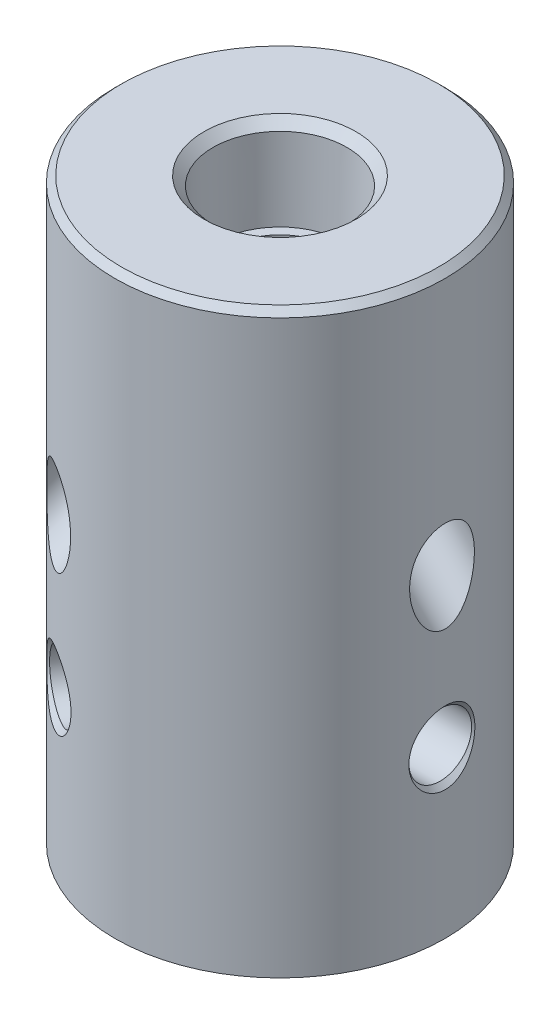
SolidWorks part; units mm, degrees
ref_plane "Plane1" through (0, 0, 0) normal (0, 0, 1) x (1, 0, 0)
ref_plane "Plane2" through (0, 0, 0) normal (0, 1, 0) x (1, 0, 0)
ref_plane "Plane3" through (0, 0, 0) normal (1, 0, 0) x (0, 0, -1)
sketch "Sketch1" plane through (0, 0, 0) normal (0, 0, 1) x (1, 0, 0)
  line L0 (0, -15.4434) -> (0, 76.0833) construction
  line L1 (0, 0) -> (2.54, 0)
  line L2 (2.54, 0) -> (12.7, 1.7915)
  line L3 (12.7, 1.7915) -> (12.7, 45.7335)
  line L4 (12.192, 46.2415) -> (0, 46.2415)
  line L5 (0, 46.2415) -> (0, 0)
  line L6 (6.35, 0.6718) -> (3.9132, 14.4915) construction
  line L7 (12.7, 14.4915) -> (3.9132, 14.4915) construction
  line L8 (12.7, 25.9215) -> (0, 38.6215) construction
  line L9 (12.7, 45.7335) -> (12.192, 46.2415)
  point P7 (12.7, 46.2415)
  dimension "D1" = 5.08
  dimension "D2" = 6.35
  dimension "D3" = 10
  dimension "D4" = 25.4
  dimension "D5" = 44.45
  dimension "D6" = 12.7
  dimension "D7" = 20.32
  dimension "D8" = 45
revolve "Revolve1" add sketch "Sketch1" angle 360 about L5
hole_wizard "1/8 NPT Tapped Hole1" positions "Sketch5" profile "Sketch4" size "1/8" standard "ANSI Inch"
sketch "Sketch5" plane through (0, 46.2415, 0) normal (0, 1, 0) x (1, 0, 0)
  point P0 (0, 0)
sketch "Sketch4" plane through (0, 46.2415, 0) normal (1, 0, 0) x (0, 0, 1)
  line L0 (0, 0) -> (0, 17.7735)
  line L1 (4.2164, 15.24) -> (0, 17.7735)
  line L2 (-4.2164, 15.24) -> (0, 17.7735) construction
  line L3 (4.2164, 15.24) -> (4.2164, 6.9342)
  line L4 (4.2164, 6.9342) -> (4.9571, 6.9342)
  line L5 (4.9571, 6.9342) -> (5.1438, 0.6982)
  line L6 (5.1438, 0.6982) -> (5.842, 0)
  line L7 (5.842, 0) -> (0, 0)
  line L8 (0, -6.35) -> (0, 107.95) construction
  line L9 (-5.1438, 0.6982) -> (-5.842, 0) construction
  line L11 (-4.2164, 6.9342) -> (-4.9571, 6.9342) construction
  line L12 (-4.9571, 6.9342) -> (-5.1438, 0.6982) construction
  dimension "Tap Drill Dia." = 8.4328
  dimension "Tap Drill Depth" = 15.24
  dimension "Thread Dia." = 10.2876
  dimension "Thread Angle" = 3.43
  dimension "Thread Depth" = 6.9342
  dimension "C'Sink Dia." = 11.684
  dimension "C'Sink Angle" = 90
  dimension "Drill Angle" = 118
hole_wizard "D (0.246) Diameter Hole1" positions "3DSketch1" profile "Sketch2" hole size "D" standard "ANSI Inch"
sketch3d "3DSketch1"
  point P3 (6.35, 0.6718, 0)
sketch "Sketch2" plane through (6.35, 0.6718, 0) normal (0, 0, 1) x (0.9848, 0.1736, 0)
  line L0 (0, 0) -> (0, 14.5772)
  line L1 (0, 14.5772) -> (3.1242, 12.7)
  line L2 (3.1242, 12.7) -> (3.1242, 0.3048)
  line L3 (3.1242, 0.3048) -> (3.429, 0)
  line L5 (3.429, 0) -> (0, 0)
  line L6 (-3.1242, 0.3048) -> (-3.429, 0) construction
  line L10 (0, 14.5772) -> (-3.1242, 12.7) construction
  line L11 (0, -6.35) -> (0, 107.95) construction
  dimension "Hole Dia." = 6.2484
  dimension "Hole Depth" = 12.7
  dimension "Near C'Sink Dia." = 6.858
  dimension "Near C'Sink Angle" = 90
  dimension "Drill Angle" = 118
hole_wizard "#10-32 Tapped Hole1" positions "3DSketch2" profile "Sketch3" tap size "#10-32" standard "ANSI Inch"
sketch3d "3DSketch2"
  point P0 (12.7, 14.4915, 0)
sketch "Sketch3" plane through (12.7, 14.4915, 0) normal (0, 1, 0) x (0, 0, -1)
  line L0 (0, 0) -> (0, 10.1033)
  line L1 (0, 10.1033) -> (2.0193, 8.89)
  line L2 (2.0193, 8.89) -> (2.0193, 5.08)
  line L3 (2.0193, 5.08) -> (2.413, 5.08)
  line L5 (2.413, 5.08) -> (2.413, 0.381)
  line L6 (2.413, 0.381) -> (2.794, 0)
  line L7 (2.794, 0) -> (0, 0)
  line L8 (-2.413, 0.381) -> (-2.794, 0) construction
  line L10 (0, 10.1033) -> (-2.0193, 8.89) construction
  line L11 (0, -6.35) -> (0, 107.95) construction
  dimension "Tap Drill Dia." = 4.0386
  dimension "Tap Drill Depth" = 8.89
  dimension "Thread Major Dia." = 4.826
  dimension "Thread Depth" = 5.08
  dimension "Near C'Sink Dia." = 5.588
  dimension "Near C'Sink Angle" = 90
  dimension "Drill Angle" = 118
sketch "Sketch7" plane through (0, 0, 0) normal (0, 0, 1) x (1, 0, 0)
  line L0 (0, 38.6215) -> (21.3461, 17.2754) construction
  line L1 (12.7, 25.9215) -> (0, 38.6215) construction
  line L2 (14.4601, 24.1614) -> (12.7, 22.4012)
  line L3 (12.7, 22.4012) -> (-0.7025, 35.8038)
  line L4 (-0.7025, 35.8038) -> (0, 38.6215)
  line L5 (0, 38.6215) -> (14.4601, 24.1614)
  line L6 (12.7, 1.7915) -> (12.7, 45.7335) construction
  dimension "D1" = 4.9784
  dimension "D2" = 59
revolve "Cut-Revolve1" cut sketch "Sketch7" angle 360 about L0
pattern_circular "CirPattern1" count 3 over 360 about axis through (0, 0, 0) along (0, 1, 0) of "D (0.246) Diameter Hole1", "#10-32 Tapped Hole1", "Cut-Revolve1"
